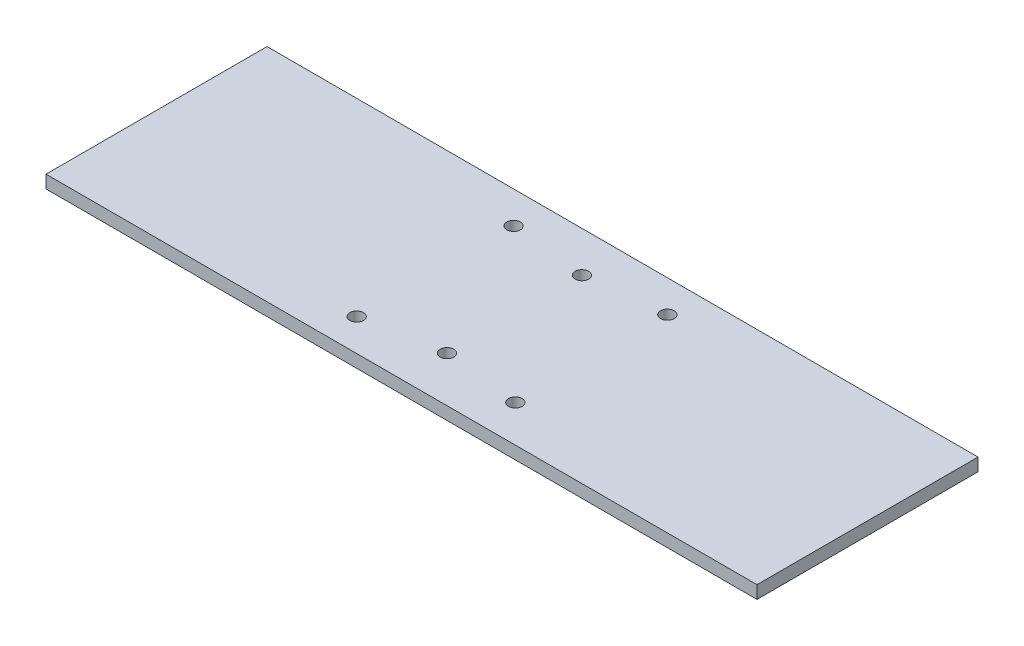
SolidWorks part; units mm, degrees
ref_plane "前视基准面" through (0, 0, 0) normal (0, 0, 1) x (1, 0, 0)
ref_plane "上视基准面" through (0, 0, 0) normal (0, 1, 0) x (1, 0, 0)
ref_plane "右视基准面" through (0, 0, 0) normal (1, 0, 0) x (0, 0, -1)
other "Configuration Table"
sketch "草图1" plane through (0, 0, 0) normal (0, 1, 0) x (1, 0, 0)
  line L1 (-83.24, 51.75) -> (83.24, 51.75)
  line L2 (-83.24, 51.75) -> (-83.24, 0)
  line L3 (-83.24, 0) -> (83.24, 0)
  line L4 (83.24, 51.75) -> (83.24, 0)
  point P4 (0, 0)
  dimension "D1" = 51.75
  dimension "D2" = 166.48
extrude "凸台-拉伸1" add sketch "草图1" along normal blind 3
sketch "草图3" plane through (0, 3, 0) normal (0, 1, 0) x (1, 0, 0)
  line L0 (83.24, 51.75) -> (-83.24, 51.75) construction
  circle A0 centre (-18, 44.25) radius 1.6
  circle A1 centre (0, 42.25) radius 1.6
  circle A2 centre (18, 44.25) radius 1.6
  point P0 (0, 42.25)
  dimension "D1" = 18
  dimension "D2" = 36
  dimension "D3" = 2
  dimension "D4" = 2
  dimension "D5" = 9.5
extrude "切除-拉伸2" cut sketch "草图3" against normal blind 10
sketch "草图4" plane through (0, 3, 0) normal (0, 1, 0) x (1, 0, 0)
  line L0 (-83.24, 0) -> (83.24, 0) construction
  circle A0 centre (0, 10.6538) radius 1.6
  circle A1 centre (18, 8.6538) radius 1.6
  circle A2 centre (-18, 7.5) radius 1.6
  point P6 (0, 0)
  point P7 (0, 0)
  point P8 (0, 0)
  point P9 (0, 0)
  point P10 (13.4042, 9.5735)
  point P11 (-6.1118, 11.0085)
  point P12 (0, 10.6538)
  point P13 (0, 0)
  point P14 (-22.9012, 0)
  dimension "D1" = 3.2
  dimension "D7" = 3.2
  dimension "D2" = 2
  dimension "D3" = 18
  dimension "D4" = 18
  dimension "D5" = 10.6538
  dimension "D6" = 7.5
extrude "切除-拉伸3" cut sketch "草图4" against normal blind 10
